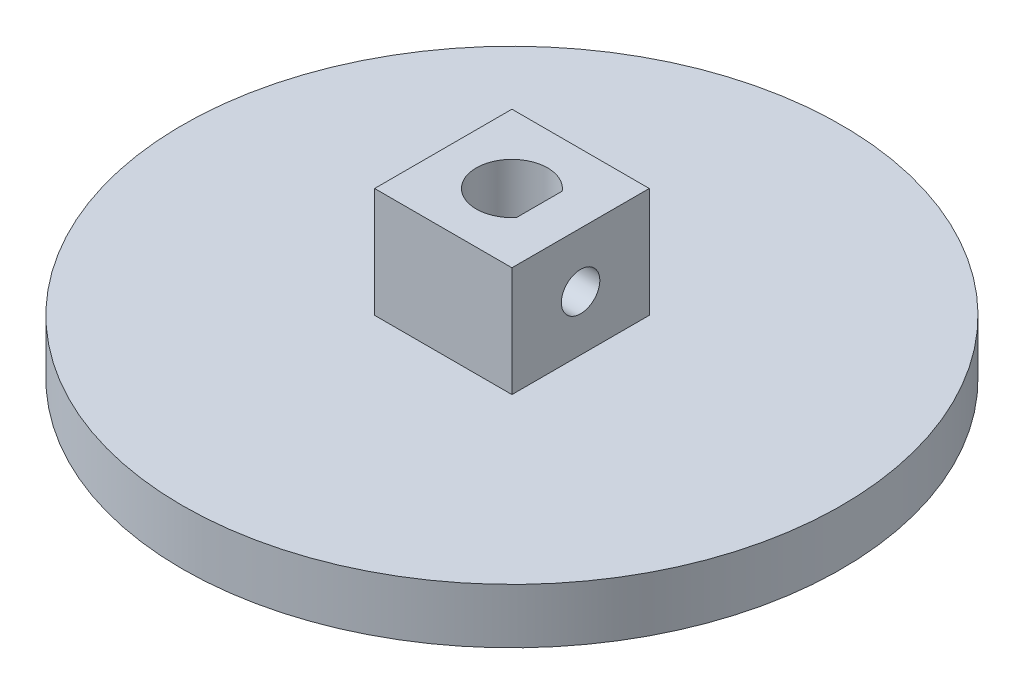
SolidWorks part; units mm, degrees
ref_plane "Front" through (0, 0, 0) normal (0, 0, 1) x (1, 0, 0)
ref_plane "Top" through (0, 0, 0) normal (0, 1, 0) x (1, 0, 0)
ref_plane "Right" through (0, 0, 0) normal (1, 0, 0) x (0, 0, -1)
sketch "Sketch1" plane through (0, 0, 0) normal (0, 1, 0) x (1, 0, 0)
  line L0 (2, 1.5) -> (2, -1.5)
  circle A0 centre (0, 0) radius 24
  arc A1 (2, 1.5) -> (2, -1.5) centre (0, 0) ccw
  point P6 (-2.5, 0)
  dimension "D1" = 48
  dimension "D2" = 5
  dimension "D3" = 4.5
extrude "Boss-Extrude1" add sketch "Sketch1" along normal blind 4
sketch "Sketch2" plane through (0, 4, 0) normal (0, 1, 0) x (1, 0, 0)
  line L1 (-5, 5) -> (5, 5)
  line L2 (-5, 5) -> (-5, -5)
  line L3 (-5, -5) -> (5, -5)
  line L4 (5, 5) -> (5, -5)
  dimension "D1" = 10
  dimension "D2" = 10
  dimension "D3" = 5
  dimension "D4" = 5
extrude "Boss-Extrude2" add sketch "Sketch2" along normal blind 8
sketch "Sketch3" plane through (0, 4, 0) normal (0, -1, 0) x (1, 0, 0)
  line L1 (2, -1.6613) -> (2, 1.6613)
  arc A1 (2, 1.6613) -> (2, -1.6613) centre (0, 0) ccw
  dimension "D1" = 5.2
sketch "Sketch4" plane through (5, 0, 0) normal (1, 0, 0) x (0, 0, -1)
  line L0 (-5, 12) -> (5, 12) construction
  line L1 (-5, 12) -> (-5, 4) construction
  circle A0 centre (0, 8) radius 1.4
  dimension "D1" = 2.8
  dimension "D2" = 4
  dimension "D3" = 5
extrude "Cut-Extrude2" cut sketch "Sketch4" against normal blind 4
extrude "Cut-Extrude3" cut sketch "Sketch3" against normal through all and the other way through all
